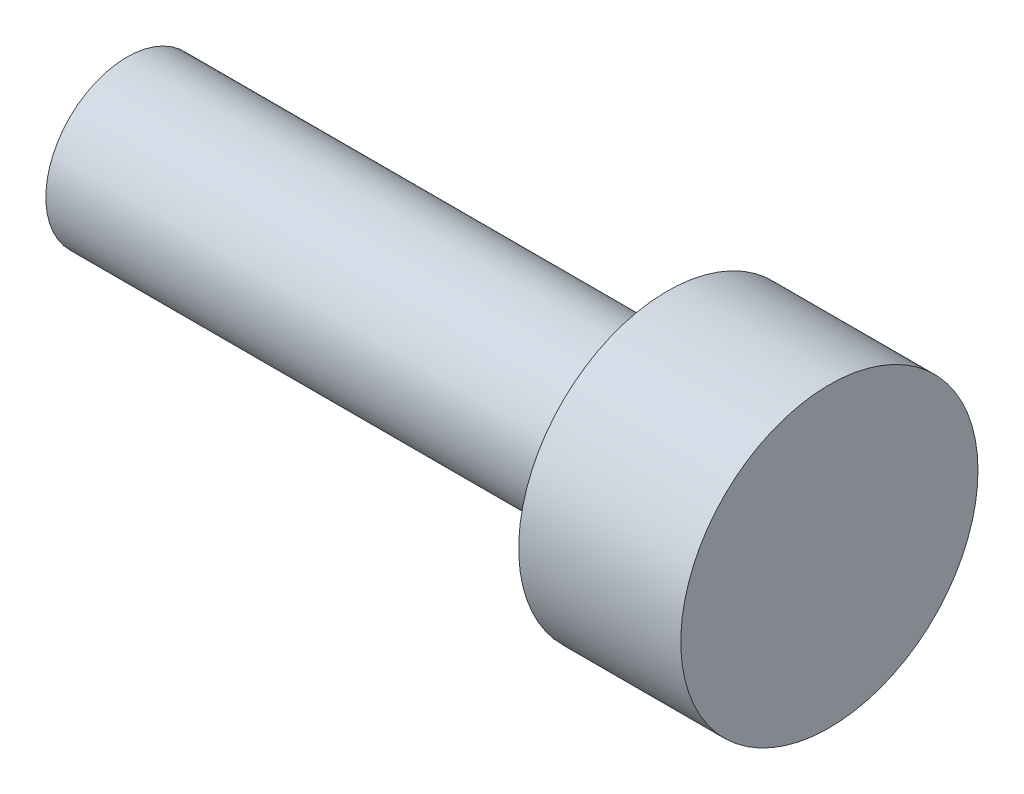
SolidWorks part; units mm, degrees
ref_plane "Front Plane" through (0, 0, 0) normal (0, 0, 1) x (1, 0, 0)
ref_plane "Top Plane" through (0, 0, 0) normal (0, 1, 0) x (1, 0, 0)
ref_plane "Right Plane" through (0, 0, 0) normal (1, 0, 0) x (0, 0, -1)
other "Configuration Table"
sketch "Sketch1" plane through (0, 0, 0) normal (1, 0, 0) x (0, 0, -1)
  circle A0 centre (0, 0) radius 2.75
extrude "head" add sketch "Sketch1" along normal blind 3 from offset 3 separate body
sketch "Sketch2" plane through (0, 0, 0) normal (1, 0, 0) x (0, 0, -1)
  circle A0 centre (0, 0) radius 1.5
extrude "shank" add sketch "Sketch2" along normal blind 10 from offset 7 separate body
